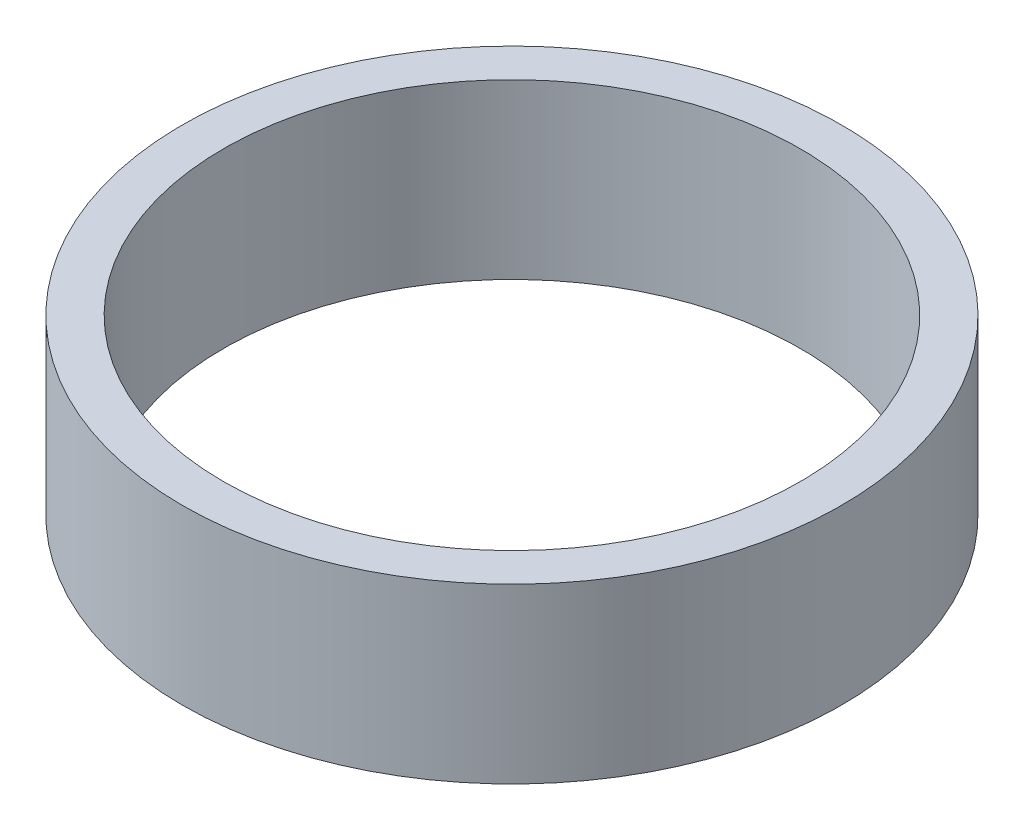
SolidWorks part; units mm, degrees
material "AISI 304"
ref_plane "Спереди" through (0, 0, 0) normal (0, 0, 1) x (1, 0, 0)
ref_plane "Сверху" through (0, 0, 0) normal (0, 1, 0) x (1, 0, 0)
ref_plane "Справа" through (0, 0, 0) normal (1, 0, 0) x (0, 0, -1)
sketch "Эскиз1" plane through (0, 0, 0) normal (0, 1, 0) x (1, 0, 0)
  circle A0 centre (0, 0) radius 40
  circle A1 centre (0, 0) radius 35
  dimension "D1" = 80
  dimension "D2" = 70
extrude "Бобышка-Вытянуть1" add sketch "Эскиз1" along normal blind 21
